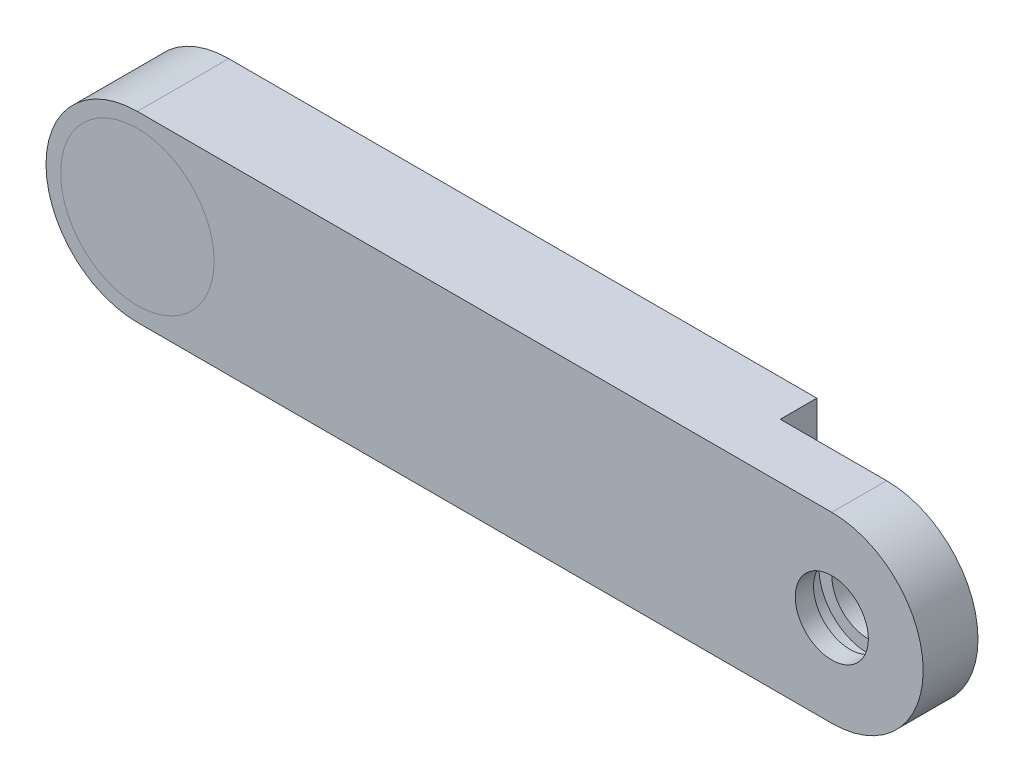
SolidWorks part; units mm, degrees
ref_plane "Front Plane" through (0, 0, 0) normal (0, 0, 1) x (1, 0, 0)
ref_plane "Top Plane" through (0, 0, 0) normal (0, 1, 0) x (1, 0, 0)
ref_plane "Right Plane" through (0, 0, 0) normal (1, 0, 0) x (0, 0, -1)
sketch "Sketch1" plane through (0, 0, 0) normal (0, 0, 1) x (1, 0, 0)
  line L0 (-154.9449, 0) -> (35.0551, 0) construction
  line L1 (-154.9449, 25) -> (35.0551, 25)
  line L2 (-154.9449, -25) -> (35.0551, -25)
  arc A0 (-154.9449, 25) -> (-154.9449, -25) centre (-154.9449, 0) ccw
  arc A1 (35.0551, -25) -> (35.0551, 25) centre (35.0551, 0) ccw
  point P3 (-59.9449, 0)
  point P8 (-179.9449, 0)
  point P9 (60.0551, 0)
  dimension "D2" = 25
  dimension "D1" = 240
extrude "Boss-Extrude1" add sketch "Sketch1" along normal blind 25
sketch "Sketch2" plane through (0, 0, 25) normal (0, 0, 1) x (1, 0, 0)
  circle A0 centre (35.0551, 0) radius 13.5
  dimension "D1" = 27
extrude "Cut-Extrude1" cut sketch "Sketch2" against normal blind 25
sketch "Sketch3" plane through (0, 0, 25) normal (0, 0, 1) x (1, 0, 0)
  circle A0 centre (-154.9449, 0) radius 21
  dimension "D1" = 42
extrude "Cut-Extrude2" cut sketch "Sketch3" against normal blind 25
sketch "Sketch4" plane through (0, 0, 25) normal (0, 0, 1) x (1, 0, 0)
  circle A0 centre (35.0551, 0) radius 13.5
  circle A1 centre (35.0551, 0) radius 10
  dimension "D1" = 20
extrude "Boss-Extrude2" add sketch "Sketch4" against normal blind 5
sketch "Sketch5" plane through (0, 0, 0) normal (0, 0, -1) x (-1, 0, 0)
  circle A0 centre (-35.0551, 0) radius 13.5
  circle A1 centre (-35.0551, 0) radius 10
extrude "Boss-Extrude3" add sketch "Sketch5" against normal blind 15
sketch "Sketch6" plane through (0, 0, 0) normal (0, 0, -1) x (-1, 0, 0)
  line L0 (-35.0551, 25) -> (-5.9572, 25)
  line L1 (-35.0551, 25) -> (154.9449, 25) construction
  line L2 (-35.0551, -25) -> (-5.9572, -25)
  line L3 (154.9449, -25) -> (-35.0551, -25) construction
  line L4 (-5.9572, -25) -> (-5.9572, 25)
  arc A0 (-35.0551, 25) -> (-35.0551, -25) centre (-35.0551, 0) ccw
extrude "Cut-Extrude3" cut sketch "Sketch6" against normal blind 10
sketch "Sketch7" plane through (0, 0, 25) normal (0, 0, 1) x (1, 0, 0)
  circle A0 centre (-154.9449, 0) radius 21
extrude "Boss-Extrude4" add sketch "Sketch7" against normal blind 3 separate body
